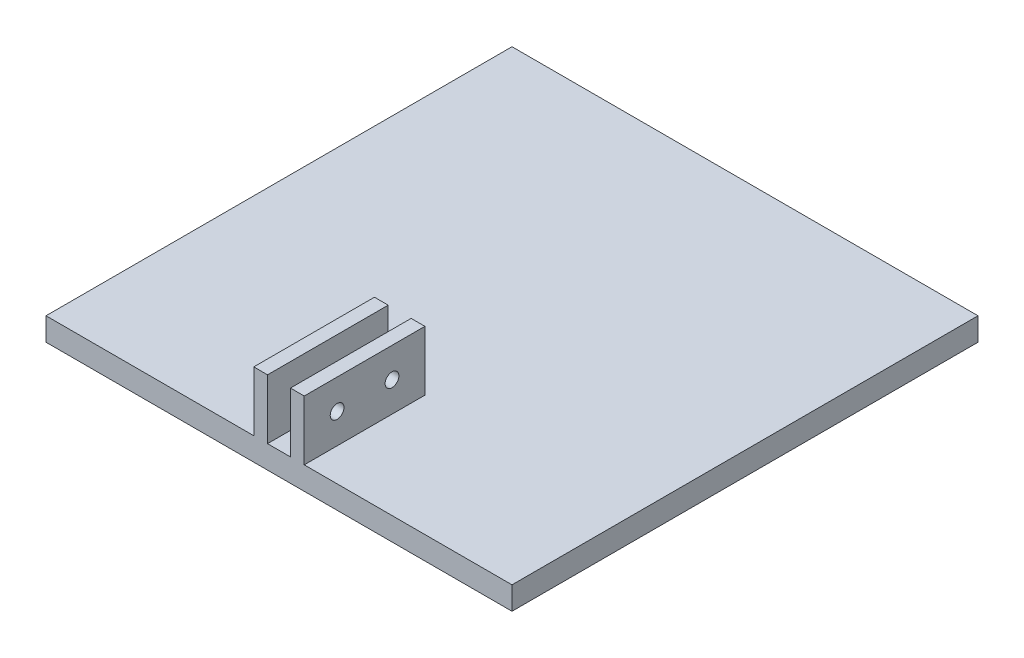
SolidWorks part; units mm, degrees
ref_plane "Front Plane" through (0, 0, 0) normal (0, 0, 1) x (1, 0, 0)
ref_plane "Top Plane" through (0, 0, 0) normal (0, 1, 0) x (1, 0, 0)
ref_plane "Right Plane" through (0, 0, 0) normal (1, 0, 0) x (0, 0, -1)
sketch "Sketch1" plane through (0, 0, 0) normal (0, 1, 0) x (1, 0, 0)
  line L1 (50.8, -50.8) -> (-50.8, -50.8)
  line L2 (50.8, -50.8) -> (50.8, 50.8)
  line L3 (50.8, 50.8) -> (-50.8, 50.8)
  line L4 (-50.8, -50.8) -> (-50.8, 50.8)
  line L5 (50.8, -50.8) -> (-50.8, 50.8) construction
  line L6 (50.8, 50.8) -> (-50.8, -50.8) construction
  point P0 (0, 0)
  dimension "D1" = 101.6
  dimension "D2" = 101.6
extrude "Boss-Extrude1" add sketch "Sketch1" along normal blind 5
sketch "Sketch2" plane through (0, 5, 0) normal (0, 1, 0) x (1, 0, 0)
  line L0 (0, 82.8298) -> (0, -82.8298) construction
  line L1 (0, -50.8) -> (2.5, -50.8) construction
  line L2 (-50.8, -50.8) -> (50.8, -50.8) construction
  line L3 (-2.5, -24.49) -> (-5.5, -24.49)
  line L4 (2.5, -50.8) -> (5.5, -50.8)
  line L5 (2.5, -50.8) -> (2.5, -24.49)
  line L6 (2.5, -24.49) -> (5.5, -24.49)
  line L7 (5.5, -50.8) -> (5.5, -24.49)
  line L8 (-5.5, -50.8) -> (-5.5, -24.49)
  line L9 (-2.5, -50.8) -> (-5.5, -50.8)
  line L10 (-2.5, -50.8) -> (-2.5, -24.49)
  point P4 (0, 0)
  dimension "D1" = 2.5
  dimension "D2" = 3
  dimension "D3" = 26.31
extrude "Boss-Extrude2" add sketch "Sketch2" along normal blind 13
sketch "Sketch3" plane through (5.5, 0, 0) normal (1, 0, 0) x (0, 0, -1)
  line L0 (-50.8, 11.5) -> (-43.63, 11.5) construction
  line L1 (-50.8, 18) -> (-50.8, 5) construction
  line L2 (-24.49, 18) -> (-24.49, 5) construction
  line L3 (-24.49, 11.5) -> (-31.66, 11.5) construction
  circle A0 centre (-43.63, 11.5) radius 1.5
  circle A1 centre (-31.66, 11.5) radius 1.5
  dimension "D2" = 3
  dimension "D1" = 7.17
extrude "Cut-Extrude1" cut sketch "Sketch3" against normal blind 13
